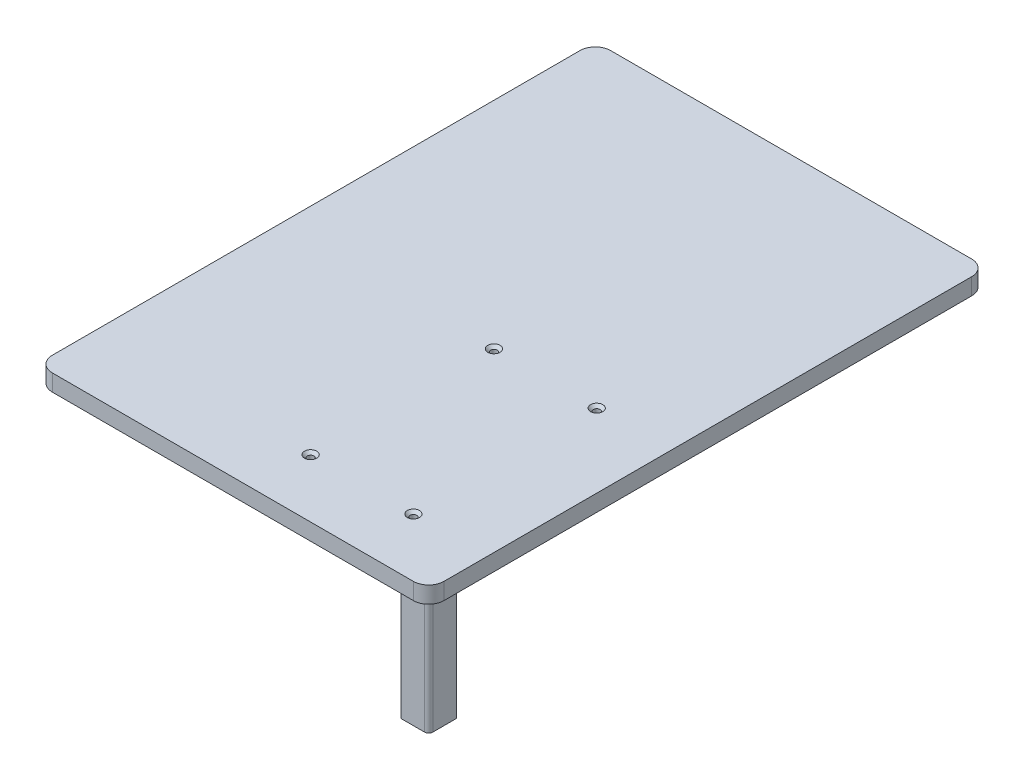
SolidWorks part; units mm, degrees
ref_plane "Alzado" through (0, 0, 0) normal (0, 0, 1) x (1, 0, 0)
ref_plane "Planta" through (0, 0, 0) normal (0, 1, 0) x (1, 0, 0)
ref_plane "Vista lateral" through (0, 0, 0) normal (1, 0, 0) x (0, 0, -1)
sketch "Croquis1" plane through (0, 81, 0) normal (0, 1, 0) x (1, 0, 0)
  line L8 (161.5, -35) -> (161.5, -58) construction
  line L9 (157.5, -35) -> (157.5, -58) construction
  line L10 (164.5, -35) -> (164.5, -58)
  line L11 (164.5, -95) -> (164.5, -58)
  line L14 (29, -100.5) -> (159, -100.5)
  line L15 (23.5, 95) -> (23.5, -95)
  line L16 (159, 100.5) -> (29, 100.5)
  line L18 (164.5, -35) -> (164.5, 95)
  line L37 (161.5, -35) -> (161.5, 95)
  line L38 (159, 97.5) -> (29, 97.5)
  line L39 (26.5, 95) -> (26.5, -95)
  line L40 (29, -97.5) -> (159, -97.5)
  line L41 (161.5, -95) -> (161.5, -58)
  line L42 (161.5, -58) -> (157.5, -58)
  line L43 (157.5, -58) -> (157.5, -91)
  line L44 (155, -93.5) -> (33, -93.5)
  line L45 (30.5, -91) -> (30.5, 91)
  line L46 (33, 93.5) -> (155, 93.5)
  line L47 (157.5, 91) -> (157.5, -35)
  line L48 (157.5, -35) -> (161.5, -35)
  line L49 (161.5, -35) -> (161.5, 95) construction
  line L50 (159, 97.5) -> (29, 97.5) construction
  line L51 (26.5, 95) -> (26.5, -95) construction
  line L52 (29, -97.5) -> (159, -97.5) construction
  line L53 (161.5, -95) -> (161.5, -58) construction
  line L55 (157.5, -58) -> (157.5, -91) construction
  line L56 (155, -93.5) -> (33, -93.5) construction
  line L57 (30.5, -91) -> (30.5, 91) construction
  line L58 (33, 93.5) -> (155, 93.5) construction
  line L59 (157.5, 91) -> (157.5, -35) construction
  arc A0 (159, -100.5) -> (164.5, -95) centre (159, -95) ccw
  arc A1 (23.5, -95) -> (29, -100.5) centre (29, -95) ccw
  arc A2 (29, 100.5) -> (23.5, 95) centre (29, 95) ccw
  arc A3 (164.5, 95) -> (159, 100.5) centre (159, 95) ccw
  arc A4 (161.5, 95) -> (159, 97.5) centre (159, 95) ccw
  arc A5 (29, 97.5) -> (26.5, 95) centre (29, 95) ccw
  arc A6 (26.5, -95) -> (29, -97.5) centre (29, -95) ccw
  arc A7 (159, -97.5) -> (161.5, -95) centre (159, -95) ccw
  arc A8 (161.5, 95) -> (159, 97.5) centre (159, 95) ccw construction
  arc A9 (29, 97.5) -> (26.5, 95) centre (29, 95) ccw construction
  arc A10 (26.5, -95) -> (29, -97.5) centre (29, -95) ccw construction
  arc A11 (159, -97.5) -> (161.5, -95) centre (159, -95) ccw construction
  arc A20 (155, -93.5) -> (157.5, -91) centre (155, -91) ccw
  arc A21 (155, -93.5) -> (157.5, -91) centre (155, -91) ccw construction
  arc A22 (30.5, -91) -> (33, -93.5) centre (33, -91) ccw
  arc A23 (30.5, -91) -> (33, -93.5) centre (33, -91) ccw construction
  arc A24 (33, 93.5) -> (30.5, 91) centre (33, 91) ccw
  arc A25 (33, 93.5) -> (30.5, 91) centre (33, 91) ccw construction
  arc A26 (157.5, 91) -> (155, 93.5) centre (155, 91) ccw
  arc A27 (157.5, 91) -> (155, 93.5) centre (155, 91) ccw construction
  dimension "D1" = 0
  dimension "D2" = 3
extrude "Saliente-Extruir1" add sketch "Croquis1" along normal blind 3
sketch "Croquis2" plane through (0, 81, 0) normal (0, 1, 0) x (1, 0, 0)
  line L4 (164.5, -95) -> (164.5, 95)
  line L5 (164.5, -95) -> (164.5, 95)
  line L6 (159, 100.5) -> (29, 100.5)
  line L7 (159, 100.5) -> (29, 100.5)
  line L12 (162.5, -95) -> (162.5, 95)
  line L13 (159, 98.5) -> (29, 98.5)
  line L14 (25.5, 95) -> (25.5, -95)
  line L15 (29, -98.5) -> (159, -98.5)
  line L16 (23.5, 95) -> (23.5, -95)
  line L17 (23.5, 95) -> (23.5, -95)
  line L18 (29, -100.5) -> (159, -100.5)
  line L19 (29, -100.5) -> (159, -100.5)
  arc A0 (162.5, 95) -> (159, 98.5) centre (159, 95) ccw
  arc A1 (29, 98.5) -> (25.5, 95) centre (29, 95) ccw
  arc A2 (25.5, -95) -> (29, -98.5) centre (29, -95) ccw
  arc A3 (159, -98.5) -> (162.5, -95) centre (159, -95) ccw
  arc A4 (164.5, 95) -> (159, 100.5) centre (159, 95) ccw
  arc A5 (164.5, 95) -> (159, 100.5) centre (159, 95) ccw
  arc A6 (29, 100.5) -> (23.5, 95) centre (29, 95) ccw
  arc A7 (29, 100.5) -> (23.5, 95) centre (29, 95) ccw
  arc A8 (23.5, -95) -> (29, -100.5) centre (29, -95) ccw
  arc A9 (23.5, -95) -> (29, -100.5) centre (29, -95) ccw
  arc A10 (159, -100.5) -> (164.5, -95) centre (159, -95) ccw
  arc A11 (159, -100.5) -> (164.5, -95) centre (159, -95) ccw
  dimension "D1" = 0
  dimension "D2" = 2
extrude "Saliente-Extruir2" add sketch "Croquis2" against normal blind 3
sketch "Croquis4" plane through (0, 81, 0) normal (0, -1, 0) x (1, 0, 0)
  line L6 (33.5, -90.5) -> (154.5, -90.5)
  line L7 (154.5, -90.5) -> (154.5, 35)
  line L8 (154.5, 35) -> (154.5, 58)
  line L9 (154.5, 58) -> (154.5, 90.5)
  line L10 (154.5, 90.5) -> (33.5, 90.5)
  line L11 (33.5, 90.5) -> (33.5, -90.5)
  line L12 (33, -92.5) -> (155, -92.5)
  line L13 (156.5, -91) -> (156.5, 35)
  line L14 (156.5, 35) -> (156.5, 58)
  line L15 (156.5, 58) -> (156.5, 91)
  line L16 (31.5, 91) -> (31.5, -91)
  line L17 (155, 92.5) -> (33, 92.5)
  line L18 (33, -92.5) -> (155, -92.5)
  line L19 (156.5, -91) -> (156.5, 35)
  line L20 (156.5, 35) -> (156.5, 58)
  line L21 (156.5, 58) -> (156.5, 91)
  line L22 (31.5, 91) -> (31.5, -91)
  line L23 (155, 92.5) -> (33, 92.5)
  arc A4 (154.5, -90.5) -> (154.5, -90.5) centre (154.5, -90.5) ccw
  arc A5 (154.5, 90.5) -> (154.5, 90.5) centre (154.5, 90.5) ccw
  arc A6 (33.5, 90.5) -> (33.5, 90.5) centre (33.5, 90.5) ccw
  arc A7 (33.5, -90.5) -> (33.5, -90.5) centre (33.5, -90.5) ccw
  arc A8 (31.5, -91) -> (33, -92.5) centre (33, -91) ccw
  arc A9 (155, -92.5) -> (156.5, -91) centre (155, -91) ccw
  arc A10 (156.5, 91) -> (155, 92.5) centre (155, 91) ccw
  arc A11 (33, 92.5) -> (31.5, 91) centre (33, 91) ccw
  arc A12 (31.5, -91) -> (33, -92.5) centre (33, -91) ccw
  arc A13 (155, -92.5) -> (156.5, -91) centre (155, -91) ccw
  arc A14 (156.5, 91) -> (155, 92.5) centre (155, 91) ccw
  arc A15 (33, 92.5) -> (31.5, 91) centre (33, 91) ccw
  dimension "D1" = 1
  dimension "D2" = 2
extrude "Saliente-Extruir4" add sketch "Croquis4" along normal blind 3
sketch "Croquis5" plane through (0, 81, 0) normal (0, -1, 0) x (1, 0, 0)
  line L22 (156.5, -91) -> (156.5, 91) construction
  line L24 (155, 92.5) -> (146.5, 92.5)
  line L25 (155, 92.5) -> (33, 92.5) construction
  line L26 (146.5, 92.5) -> (146.5, 82.5)
  line L27 (146.5, 82.5) -> (156.5, 82.5)
  line L28 (156.5, 82.5) -> (156.5, 91)
  line L29 (31.5, -91) -> (31.5, -82.5)
  line L30 (31.5, 91) -> (31.5, -91) construction
  line L31 (31.5, -82.5) -> (41.5, -82.5)
  line L32 (41.5, -82.5) -> (41.5, -92.5)
  line L33 (33, -92.5) -> (155, -92.5) construction
  line L34 (41.5, -92.5) -> (33, -92.5)
  arc A4 (156.5, 91) -> (155, 92.5) centre (155, 91) ccw construction
  arc A5 (156.5, 91) -> (155, 92.5) centre (155, 91) ccw
  arc A6 (31.5, -91) -> (33, -92.5) centre (33, -91) ccw construction
  arc A7 (31.5, -91) -> (33, -92.5) centre (33, -91) ccw
  dimension "D1" = 10
  dimension "D2" = 10
  dimension "D3" = 10
  dimension "D4" = 10
extrude "Saliente-Extruir5" add sketch "Croquis5" along normal blind 50
sketch "Croquis7" plane through (0, 84, 0) normal (0, 1, 0) x (1, 0, 0)
  circle A0 centre (101, -79.5) radius 1.2 construction
  circle A1 centre (138, -79.5) radius 1.2 construction
  circle A2 centre (101, -13.5) radius 1.2 construction
  circle A3 centre (138, -13.5) radius 1.2 construction
  circle A4 centre (101, -79.5) radius 1.2
  circle A5 centre (138, -79.5) radius 1.2
  circle A6 centre (101, -13.5) radius 1.2
  circle A7 centre (138, -13.5) radius 1.2
hole_wizard "Avellanado para tornillo con cabeza plana de M21" positions "Croquis8" profile "Croquis10" countersink size "M2" standard "Ansi Metric" end condition up to next
sketch "Croquis8" plane through (0, 84, 0) normal (0, 1, 0) x (1, 0, 0)
  point P0 (138, -13.5)
  point P3 (101, -13.5)
  point P6 (138, -79.5)
  point P9 (101, -79.5)
sketch "Croquis10" plane through (138, 84, 13.5) normal (1, 0, 0) x (0, 0, 1)
  line L0 (0, 0) -> (0, 3)
  line L1 (0, 3) -> (1.2, 3)
  line L2 (1.2, 3) -> (1.2, 1)
  line L3 (1.2, 1) -> (2.2, 0)
  line L5 (2.2, 0) -> (0, 0)
  line L6 (-1.2, 1) -> (-2.2, 0) construction
  line L11 (0, -6.35) -> (0, 107.95) construction
  dimension "Diámetro de taladro hasta el siguiente" = 2.4
  dimension "Profundidad de taladro hasta el siguiente" = 3
  dimension "Diámetro de avellanado cercano" = 4.4
  dimension "Ángulo de avellanado cercano" = 90
sketch "Croquis11" plane through (0, 31, 0) normal (0, -1, 0) x (1, 0, 0)
  line L0 (146.5, 92.5) -> (156.5, 82.5) construction
  line L1 (31.5, -82.5) -> (41.5, -92.5) construction
  circle A0 centre (36.5, -87.5) radius 2
  circle A1 centre (151.5, 87.5) radius 2
  dimension "D1" = 4
extrude "Cortar-Extruir2" cut sketch "Croquis11" against normal blind 6
chamfer "Chaflán2" distance 0.3 angle 45 2 edges at (151.5, 31, 85.5) (36.5, 31, -89.5)
